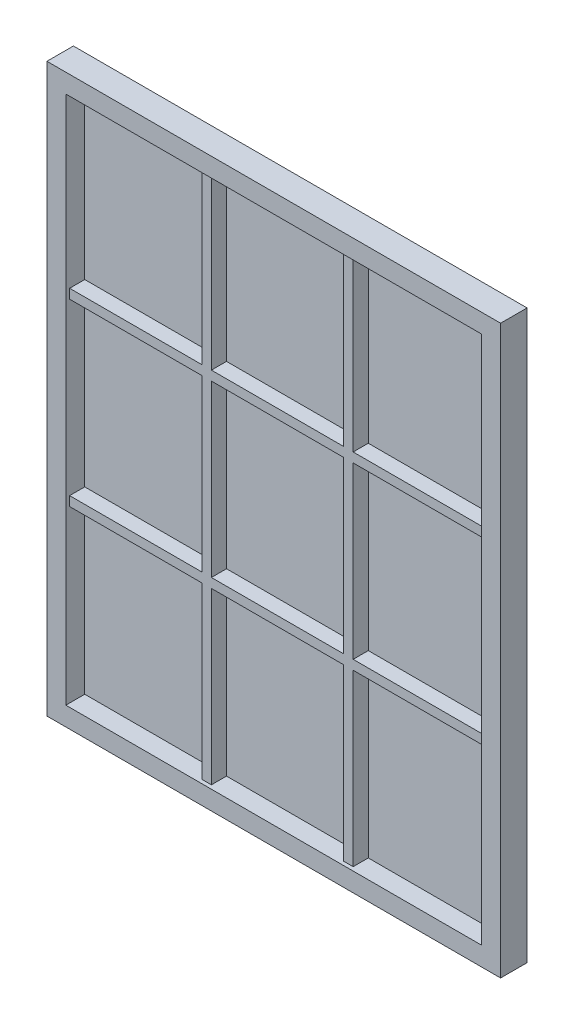
SolidWorks part; units mm, degrees
ref_plane "Front Plane" through (0, 0, 0) normal (0, 0, 1) x (1, 0, 0)
ref_plane "Top Plane" through (0, 0, 0) normal (0, 1, 0) x (1, 0, 0)
ref_plane "Right Plane" through (0, 0, 0) normal (1, 0, 0) x (0, 0, -1)
sketch "Sketch1" plane through (0, 0, 0) normal (0, 0, 1) x (1, 0, 0)
  line L1 (0, 0) -> (304.8, 0)
  line L2 (0, 0) -> (0, 381)
  line L3 (0, 381) -> (304.8, 381)
  line L4 (304.8, 0) -> (304.8, 381)
  dimension "D1" = 381
  dimension "D2" = 304.8
extrude "Boss-Extrude1" add sketch "Sketch1" along normal blind 17.78
sketch "Sketch2" plane through (0, 0, 17.78) normal (0, 0, 1) x (1, 0, 0)
  line L0 (12.7, 127) -> (101.6, 127)
  line L1 (107.95, 368.3) -> (196.85, 368.3)
  line L2 (107.95, 368.3) -> (107.95, 254)
  line L3 (107.95, 254) -> (196.85, 254)
  line L4 (196.85, 368.3) -> (196.85, 254)
  line L37 (12.7, 368.3) -> (101.6, 368.3)
  line L38 (12.7, 368.3) -> (12.7, 254)
  line L39 (12.7, 254) -> (101.6, 254)
  line L40 (101.6, 368.3) -> (101.6, 254)
  line L41 (203.2, 368.3) -> (292.1, 368.3)
  line L42 (203.2, 368.3) -> (203.2, 254)
  line L43 (203.2, 254) -> (292.1, 254)
  line L44 (292.1, 368.3) -> (292.1, 254)
  line L45 (0, 381) -> (0, 0) construction
  line L46 (304.8, 381) -> (0, 381) construction
  line L47 (304.8, 0) -> (304.8, 381) construction
  line L48 (12.7, 247.65) -> (101.6, 247.65)
  line L49 (12.7, 247.65) -> (12.7, 133.35)
  line L50 (12.7, 133.35) -> (101.6, 133.35)
  line L51 (101.6, 247.65) -> (101.6, 133.35)
  line L52 (107.95, 247.65) -> (196.85, 247.65)
  line L53 (107.95, 247.65) -> (107.95, 133.35)
  line L54 (107.95, 133.35) -> (196.85, 133.35)
  line L55 (196.85, 247.65) -> (196.85, 133.35)
  line L56 (203.2, 247.65) -> (292.1, 247.65)
  line L57 (203.2, 247.65) -> (203.2, 133.35)
  line L58 (203.2, 133.35) -> (292.1, 133.35)
  line L59 (292.1, 247.65) -> (292.1, 133.35)
  line L60 (12.7, 127) -> (12.7, 12.7)
  line L61 (12.7, 12.7) -> (101.6, 12.7)
  line L62 (101.6, 127) -> (101.6, 12.7)
  line L63 (107.95, 127) -> (196.85, 127)
  line L64 (107.95, 127) -> (107.95, 12.7)
  line L65 (107.95, 12.7) -> (196.85, 12.7)
  line L66 (196.85, 127) -> (196.85, 12.7)
  line L67 (203.2, 127) -> (292.1, 127)
  line L68 (203.2, 127) -> (203.2, 12.7)
  line L69 (203.2, 12.7) -> (292.1, 12.7)
  line L70 (292.1, 127) -> (292.1, 12.7)
  line L71 (0, 0) -> (304.8, 0) construction
  dimension "D1" = 114.3
  dimension "D2" = 88.9
  dimension "D3" = 12.7
  dimension "D4" = 12.7
  dimension "D5" = 114.3
  dimension "D6" = 88.9
  dimension "D7" = 6.35
  dimension "D8" = 12.7
  dimension "D9" = 6.35
  dimension "D10" = 12.7
  dimension "D11" = 12.7
  dimension "D12" = 114.3
  dimension "D13" = 6.35
  dimension "D14" = 12.7
  dimension "D15" = 6.35
  dimension "D16" = 6.35
  dimension "D17" = 114.3
  dimension "D18" = 114.3
  dimension "D19" = 88.9
  dimension "D20" = 88.9
  dimension "D21" = 6.35
  dimension "D22" = 6.35
  dimension "D23" = 12.7
  dimension "D24" = 114.3
  dimension "D25" = 12.7
  dimension "D26" = 12.7
  dimension "D27" = 88.9
  dimension "D28" = 114.3
  dimension "D29" = 6.35
  dimension "D30" = 88.9
  dimension "D31" = 6.35
  dimension "D32" = 114.3
  dimension "D33" = 6.35
  dimension "D34" = 6.35
  dimension "D35" = 88.9
  dimension "D36" = 114.3
extrude "Cut-Extrude1" cut sketch "Sketch2" against normal blind 12.7
sketch "Sketch3" plane through (0, 0, 17.78) normal (0, 0, 1) x (1, 0, 0)
  line L1 (12.7, 12.7) -> (292.1, 12.7)
  line L2 (12.7, 12.7) -> (12.7, 368.3)
  line L3 (12.7, 368.3) -> (292.1, 368.3)
  line L4 (292.1, 12.7) -> (292.1, 368.3)
extrude "Cut-Extrude2" cut sketch "Sketch3" against normal blind 2.54
sketch "Sketch4" plane through (0, 0, 0) normal (0, 0, -1) x (-1, 0, 0)
  line L0 (-304.8, 381) -> (0, 381) construction
  line L1 (-304.8, 0) -> (-304.8, 381) construction
  line L2 (0, 381) -> (0, 0) construction
  circle A0 centre (-6.35, 374.65) radius 1.27
  circle A1 centre (-298.45, 374.65) radius 1.27
  dimension "D5" = 2.54
  dimension "D6" = 2.54
  dimension "D1" = 6.35
  dimension "D2" = 6.35
  dimension "D3" = 6.35
  dimension "D4" = 6.35
extrude "Cut-Extrude3" cut sketch "Sketch4" against normal blind 12.7
